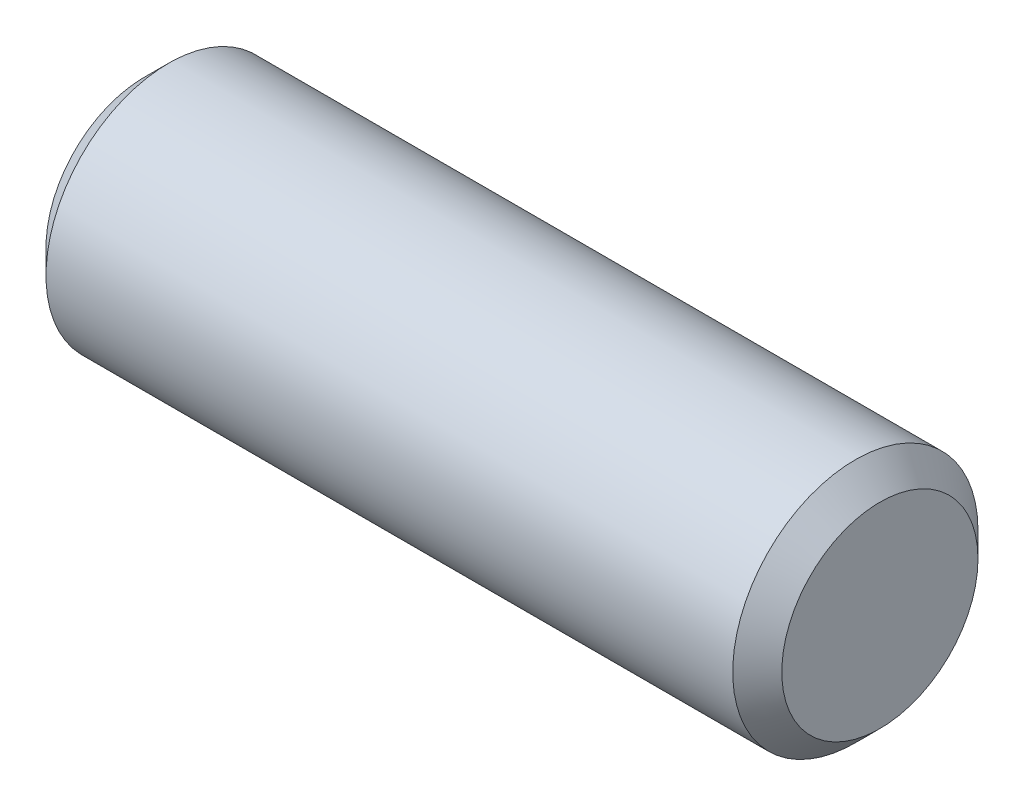
SolidWorks part; units mm, degrees
ref_plane "Front" through (0, 0, 0) normal (0, 0, 1) x (1, 0, 0)
ref_plane "Top" through (0, 0, 0) normal (0, 1, 0) x (1, 0, 0)
ref_plane "Right" through (0, 0, 0) normal (1, 0, 0) x (0, 0, -1)
sketch "Sketch1" plane through (0, 0, 0) normal (0, 0, 1) x (1, 0, 0)
  line L0 (-1.1906, 0) -> (1.1906, 0) construction
  line L1 (1.1906, 0.3969) -> (1.1906, -0.3969) construction
  line L2 (-1.1906, 0.3969) -> (-1.1906, -0.3969) construction
  dimension "Length" = 2.3813
  dimension "Diameter" = 0.7937
sketch "Sketch2" plane through (0, 0, 0) normal (1, 0, 0) x (0, 0, -1)
  circle A0 centre (0, 0) radius 0.3969
extrude "Extrude1" add sketch "Sketch2" against normal up to vertex (1.1906 mm away) and the other way up to vertex (1.1906 mm away) up to point (-1.1906, 0.3969, 0) other way up to point (1.1906, 0.3969, 0)
chamfer "Chamfer1" distance 0.0794 angle 45 2 edges at (1.1906, 0, -0.3969) (-1.1906, 0, -0.3969)
equation "\"D1@Chamfer1\" = \"Diameter@Sketch1\"*.1"
